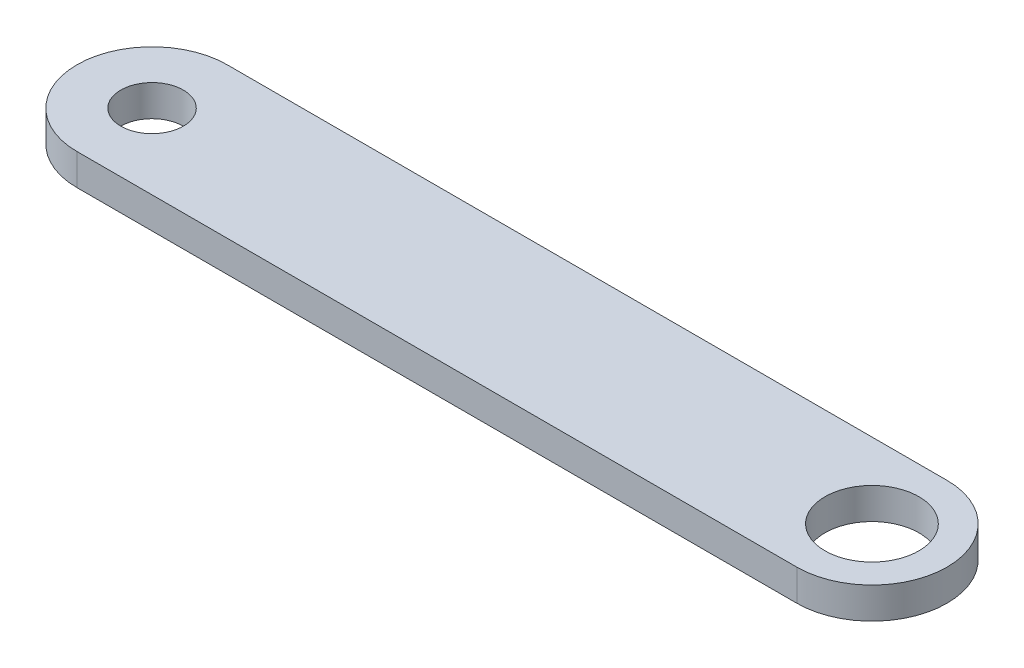
SolidWorks part; units mm, degrees
ref_plane "Front Plane" through (0, 0, 0) normal (0, 0, 1) x (1, 0, 0)
ref_plane "Top Plane" through (0, 0, 0) normal (0, 1, 0) x (1, 0, 0)
ref_plane "Right Plane" through (0, 0, 0) normal (1, 0, 0) x (0, 0, -1)
sketch "Sketch1" plane through (0, 0, 0) normal (0, 1, 0) x (1, 0, 0)
  line L0 (-57.5, 0) -> (57.5, 0) construction
  line L1 (-57.5, 12) -> (57.5, 12)
  line L2 (-57.5, -12) -> (57.5, -12)
  arc A0 (-57.5, 12) -> (-57.5, -12) centre (-57.5, 0) ccw
  arc A1 (57.5, -12) -> (57.5, 12) centre (57.5, 0) ccw
  circle A2 centre (-57.5, 0) radius 5
  circle A3 centre (57.5, 0) radius 7.5
  point P3 (0, 0)
  dimension "D2" = 12
  dimension "D3" = 10
  dimension "D4" = 15
  dimension "D1" = 115
extrude "Boss-Extrude1" add sketch "Sketch1" along normal blind 5
scale "Scale1" scale about centroid uniform scaling yes scale factor 0.25
